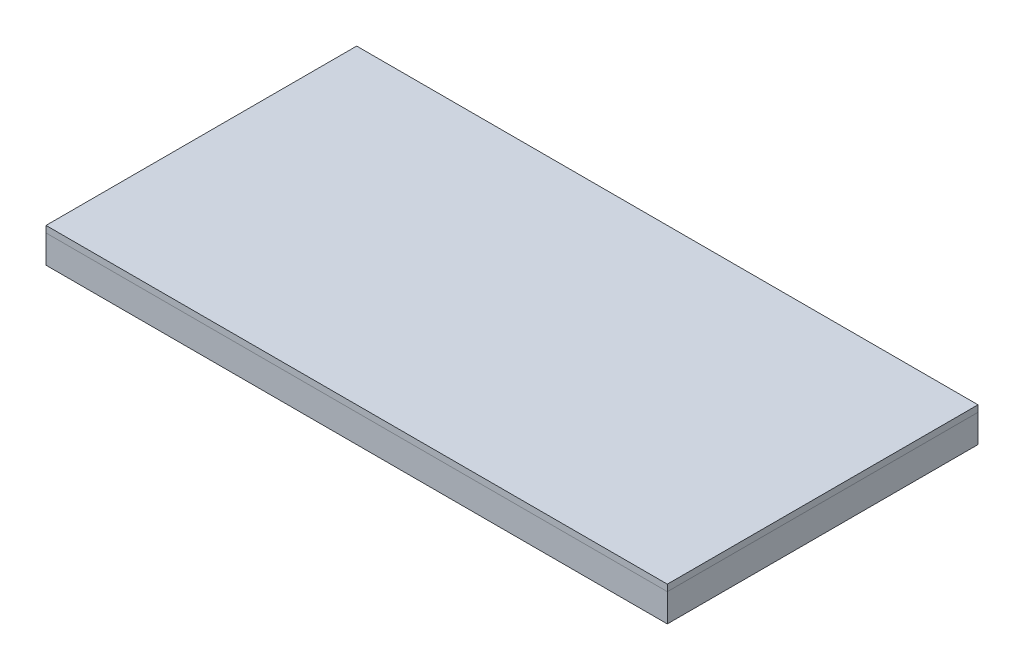
SolidWorks part; units mm, degrees
ref_plane "Ebene vorne" through (0, 0, 0) normal (0, 0, 1) x (1, 0, 0)
ref_plane "Ebene oben" through (0, 0, 0) normal (0, 1, 0) x (1, 0, 0)
ref_plane "Ebene rechts" through (0, 0, 0) normal (1, 0, 0) x (0, 0, -1)
sketch "Skizze1" plane through (0, 0, 0) normal (0, 1, 0) x (1, 0, 0)
  line L1 (-1000, -500) -> (1000, -500)
  line L2 (-1000, -500) -> (-1000, 500)
  line L3 (-1000, 500) -> (1000, 500)
  line L4 (1000, -500) -> (1000, 500)
  line L5 (-1000, -500) -> (1000, 500) construction
  line L6 (-1000, 500) -> (1000, -500) construction
  point P0 (0, 0)
  dimension "D1" = 1000
  dimension "D2" = 2000
extrude "Aufsatz-Linear austragen2" add sketch "Skizze1" against normal blind 21
sketch "Skizze3" plane through (0, -21, 0) normal (0, -1, 0) x (1, 0, 0)
  line L0 (910, -410) -> (910, 410)
  line L1 (910, 410) -> (-910, 410)
  line L2 (-910, 410) -> (-910, -410)
  line L3 (-910, -410) -> (910, -410)
  line L4 (1000, -500) -> (1000, 500)
  line L5 (1000, 500) -> (-1000, 500)
  line L6 (-1000, 500) -> (-1000, -500)
  line L7 (-1000, -500) -> (1000, -500)
  line L8 (1000, -500) -> (1000, 500)
  line L9 (1000, 500) -> (-1000, 500)
  line L10 (-1000, 500) -> (-1000, -500)
  line L11 (-1000, -500) -> (1000, -500)
  dimension "D1" = 0
  dimension "D2" = 90
extrude "Aufsatz-Linear austragen3" add sketch "Skizze3" along normal blind 90 separate body
